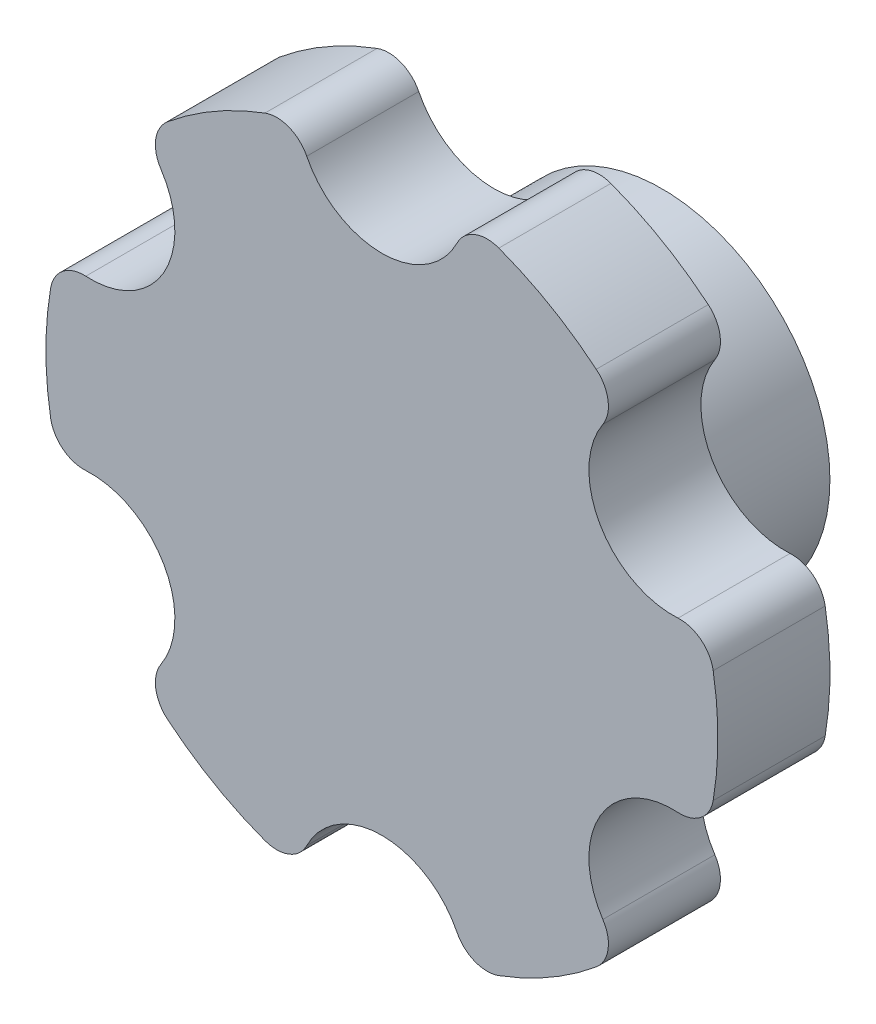
SolidWorks part; units mm, degrees
ref_plane "Ön Düzlem" through (0, 0, 0) normal (0, 0, 1) x (1, 0, 0)
ref_plane "Üst Düzlem" through (0, 0, 0) normal (0, 1, 0) x (1, 0, 0)
ref_plane "Sağ Düzlem" through (0, 0, 0) normal (1, 0, 0) x (0, 0, -1)
sketch "Çizim1" plane through (0, 0, 0) normal (0, 0, 1) x (1, 0, 0)
  circle A0 centre (0, 0) radius 15
  dimension "D1" = 30
extrude "Yükseklik-Ekstrüzyon1" add sketch "Çizim1" along normal blind 15
sketch "Çizim2" plane through (0, 0, 15) normal (0, 0, 1) x (1, 0, 0)
  circle A0 centre (0, 0) radius 30
  dimension "D1" = 60
extrude "Yükseklik-Ekstrüzyon2" add sketch "Çizim2" along normal blind 10
sketch "Çizim3" plane through (0, 0, 25) normal (0, 0, 1) x (1, 0, 0)
  circle A0 centre (0, 30) radius 7.5
  circle A1 centre (0, 0) radius 30 construction
  dimension "D1" = 15
extrude "Kes-Ekstrüzyon1" cut sketch "Çizim3" against normal blind 10
fillet "Radyus1" radius 3 2 edges at (7.4412, 29.0625, 20) (-7.4412, 29.0625, 20)
pattern_circular "Dairesel Kaplama3" count 6 over 360 about axis through (0, 0, 0) along (0, 0, 1) of "Kes-Ekstrüzyon1", "Radyus1"
sketch "Çizim4" plane through (0, 0, 0) normal (0, 0, -1) x (-1, 0, 0)
  circle A0 centre (0, 0) radius 4.25
  dimension "D1" = 8.5
extrude "Kes-Ekstrüzyon2" cut sketch "Çizim4" against normal blind 15
cosmetic thread "Kozmetik Diş Açma1" parameters "D2"=10
